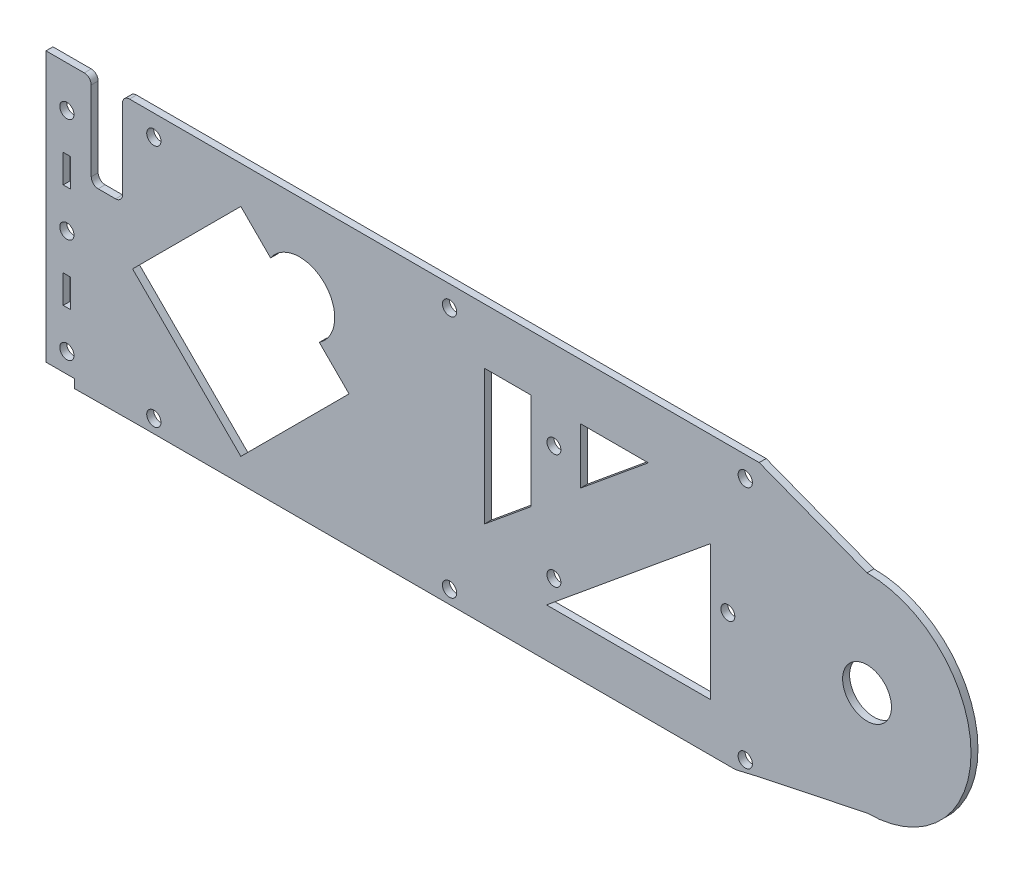
SolidWorks part; units mm, degrees
ref_plane "前视基准面" through (0, 0, 0) normal (0, 0, 1) x (1, 0, 0)
ref_plane "上视基准面" through (0, 0, 0) normal (0, 1, 0) x (1, 0, 0)
ref_plane "右视基准面" through (0, 0, 0) normal (1, 0, 0) x (0, 0, -1)
sketch "草图1" plane through (0, 0, 0) normal (0, 0, 1) x (1, 0, 0)
  line L0 (0.5429, 31.9043) -> (0.5429, 27.8043)
  line L1 (0.5429, 18.7543) -> (0.5429, 10.9543) construction
  line L2 (-0.5071, 10.8043) -> (1.5929, 10.8043)
  line L3 (-0.5071, 10.8043) -> (-0.5071, 18.9043)
  line L4 (-0.5071, 18.9043) -> (1.5929, 18.9043)
  line L5 (1.5929, 10.8043) -> (1.5929, 18.9043)
  line L6 (-0.5071, 10.8043) -> (1.5929, 18.9043) construction
  line L7 (-0.5071, 18.9043) -> (1.5929, 10.8043) construction
  line L12 (0.5429, -0.1457) -> (-5.3571, -0.1457) construction
  line L18 (50.5429, -0.1457) -> (97.8433, -0.1457) construction
  line L19 (50.5429, -0.1457) -> (230.5429, -0.1457) construction
  line L20 (200.6429, -0.1457) -> (200.6429, 38.1043) construction
  line L42 (230.5429, -30.0457) -> (199.5561, -36.5559)
  line L47 (2.6929, -38.2957) -> (-5.4571, -38.2957)
  line L49 (-5.4571, 41.7043) -> (7.5429, 41.7043)
  line L54 (199.5429, 41.7043) -> (230.5429, 29.7543)
  line L55 (7.5429, 41.7043) -> (7.5429, 14.8543)
  line L57 (7.5429, 14.8543) -> (16.5429, 14.8543)
  line L59 (-5.4571, 41.7043) -> (261.5429, 41.7043) construction
  line L60 (16.5429, 41.7043) -> (199.5429, 41.7043)
  line L61 (16.5429, 41.7043) -> (16.5429, 14.8543)
  line L62 (50.5429, 13.8543) -> (59.0992, 22.4106) construction
  line L63 (64.5429, -0.1457) -> (73.0992, 8.4106) construction
  line L64 (59.0992, 22.4106) -> (50.5429, 30.967)
  line L65 (19.4302, -0.1457) -> (50.5429, 30.967)
  line L66 (19.4302, -0.1457) -> (50.5429, -31.2584)
  line L67 (50.5429, -31.2584) -> (81.6556, -0.1457)
  line L68 (50.5429, 30.967) -> (81.6556, -0.1457) construction
  line L69 (19.4302, -0.1457) -> (81.6556, -0.1457) construction
  line L70 (50.5429, -31.2584) -> (50.5429, 30.967) construction
  line L71 (73.0992, 8.4106) -> (81.6556, -0.1457)
  line L72 (0.5429, -0.1457) -> (50.5429, -0.1457) construction
  line L73 (-0.5071, -19.1957) -> (1.5929, -11.0957) construction
  line L74 (-0.5071, -11.0957) -> (1.5929, -19.1957) construction
  line L75 (0.5429, -19.0457) -> (0.5429, -11.2457) construction
  line L76 (1.5929, -11.0957) -> (1.5929, -19.1957)
  line L77 (-0.5071, -19.1957) -> (1.5929, -19.1957)
  line L78 (-0.5071, -11.0957) -> (-0.5071, -19.1957)
  line L79 (-0.5071, -11.0957) -> (1.5929, -11.0957)
  line L80 (199.5561, -36.5559) -> (192.7469, -38.1457)
  line L81 (192.7469, -38.1457) -> (21.3658, -38.1457)
  line L82 (21.3658, -38.1457) -> (2.6929, -38.2957)
  line L83 (-5.4571, 41.7043) -> (-5.4571, -35.8026)
  line L84 (-5.4571, -35.8026) -> (2.6929, -35.8026)
  line L85 (2.6929, -35.8026) -> (2.6929, -38.2957)
  circle A0 centre (0.5429, 29.8543) radius 2.05
  circle A1 centre (0.5429, -0.1457) radius 2.05
  circle A2 centre (0.5429, -30.1457) radius 2.05
  circle A15 centre (230.5429, -0.1457) radius 7.02
  circle A16 centre (230.5429, -0.1457) radius 29.9 construction
  arc A17 (230.5429, -30.0457) -> (230.5429, 29.7543) centre (230.5429, -0.1457) ccw
  arc A19 (59.0992, 22.4106) -> (73.0992, 8.4106) centre (67.4545, 16.7659) cw
  point P6 (0.5429, 14.8543)
  point P25 (50.5429, -0.1457)
  point P67 (0.5429, -15.1457)
  dimension "D3" = 44
  dimension "D4" = 44
  dimension "D13" = 14.04
  dimension "D1" = 8.1
  dimension "D2" = 2.1
  dimension "D5" = 50
  dimension "D7" = 15
  dimension "D8" = 60
  dimension "D9" = 30
  dimension "D14" = 180
extrude "凸台-拉伸1" add sketch "草图1" along normal blind 2
sketch "草图3" plane through (0, 0, 2) normal (0, 0, 1) x (1, 0, 0)
  line L0 (16.5429, 41.7043) -> (199.5429, 41.7043) construction
  line L1 (16.5429, 41.7043) -> (16.5429, 14.8543) construction
  line L2 (148.1533, 25.7043) -> (148.1533, 9.6322)
  line L3 (110.5429, -34.2957) -> (195.5429, 35.7043) construction
  line L4 (195.5429, 35.7043) -> (195.5429, -34.2957) construction
  line L5 (195.5429, -34.2957) -> (110.5429, -34.2957) construction
  line L6 (185.5429, -24.2957) -> (138.4162, -24.2957)
  line L7 (138.4162, -24.2957) -> (185.5429, 14.5145)
  line L8 (185.5429, 14.5145) -> (185.5429, -24.2957)
  line L9 (110.5429, -34.2957) -> (110.5429, 35.7043) construction
  line L10 (110.5429, 35.7043) -> (195.5429, 35.7043) construction
  line L11 (120.5429, 25.7043) -> (167.6695, 25.7043) construction
  line L12 (120.5429, -13.1059) -> (167.6695, 25.7043) construction
  line L13 (120.5429, -13.1059) -> (120.5429, 25.7043)
  line L15 (134.0149, 25.7043) -> (134.0149, -2.0113)
  line L17 (134.0149, 25.7043) -> (120.5429, 25.7043)
  line L19 (134.0149, -2.0113) -> (120.5429, -13.1059)
  line L21 (148.1533, 25.7043) -> (167.6695, 25.7043)
  line L22 (167.6695, 25.7043) -> (148.1533, 9.6322)
  circle A0 centre (25.5429, 35.7043) radius 2.05
  circle A1 centre (110.5429, 35.7043) radius 2.05
  circle A2 centre (195.5429, 35.7043) radius 2.05
  circle A3 centre (110.5429, -34.2957) radius 2.05
  circle A4 centre (195.5429, -34.2957) radius 2.05
  circle A5 centre (25.5429, -34.2957) radius 2.05
  circle A6 centre (190.5429, -0.1457) radius 2
  circle A7 centre (140.5429, 16.3543) radius 2
  circle A8 centre (140.5429, -16.6457) radius 2
  circle A9 centre (230.5429, -0.1457) radius 2 construction
  dimension "D1" = 6
  dimension "D2" = 9
  dimension "D5" = 10
  dimension "D6" = 10
  dimension "D3" = 3
  dimension "D4" = 2
fillet "圆角1" radius 2 4 edges at (16.5429, 41.7043, 1) (7.5429, 41.7043, 1) (7.5429, 14.8543, 1) (16.5429, 14.8543, 1)
extrude "切除-拉伸1" cut sketch "草图3" against normal blind 2
